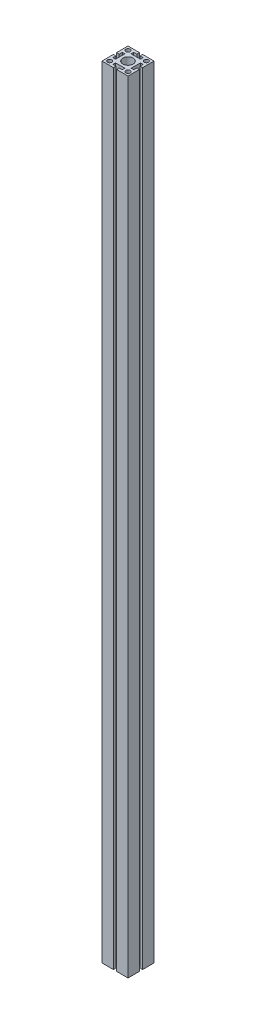
SolidWorks part; units mm, degrees
ref_plane "Front Plane" through (0, 0, 0) normal (0, 0, 1) x (1, 0, 0)
ref_plane "Top Plane" through (0, 0, 0) normal (0, 1, 0) x (1, 0, 0)
ref_plane "Right Plane" through (0, 0, 0) normal (1, 0, 0) x (0, 0, -1)
sketch "Sketch1" plane through (0, 0, 0) normal (0, 1, 0) x (1, 0, 0)
  line L1 (-25, -3) -> (-25, -25)
  line L6 (9, 20) -> (9, 15)
  line L7 (9, 20) -> (3, 20)
  line L8 (9, 15) -> (-9, 15)
  line L9 (3, 20) -> (3, 25)
  line L10 (-3, 25) -> (-25, 25)
  line L11 (-25, 25) -> (-25, 3)
  line L12 (-25, -25) -> (-3, -25)
  line L13 (25, -25) -> (25, -3)
  line L14 (3, 25) -> (25, 25)
  line L15 (-3, 20) -> (-3, 25)
  line L16 (-9, 20) -> (-9, 15)
  line L17 (3, -25) -> (25, -25)
  line L18 (25, 3) -> (25, 25)
  line L19 (-3, 20) -> (-9, 20)
  line L21 (-20, 9) -> (-15, 9)
  line L22 (-20, 9) -> (-20, 3)
  line L24 (-15, 9) -> (-15, -9)
  line L27 (-20, 3) -> (-25, 3)
  line L28 (20, -9) -> (15, -9)
  line L29 (20, -9) -> (20, -3)
  line L30 (15, -9) -> (15, 9)
  line L31 (20, -3) -> (25, -3)
  line L32 (20, 3) -> (25, 3)
  line L33 (-20, -3) -> (-25, -3)
  line L34 (20, 9) -> (15, 9)
  line L35 (20, 3) -> (20, 9)
  line L40 (-20, -9) -> (-15, -9)
  line L41 (-20, -3) -> (-20, -9)
  line L42 (-9, -20) -> (-9, -15)
  line L43 (-9, -20) -> (-3, -20)
  line L44 (-9, -15) -> (9, -15)
  line L45 (-3, -20) -> (-3, -25)
  line L46 (3, -20) -> (3, -25)
  line L47 (9, -20) -> (9, -15)
  line L48 (3, -20) -> (9, -20)
  circle A0 centre (0, 0) radius 10
  circle A1 centre (-17.6777, 17.6777) radius 4.1387
  circle A2 centre (17.6777, 17.6777) radius 4.1387
  circle A3 centre (17.6777, -17.6777) radius 4.1387
  circle A4 centre (-17.6777, -17.6777) radius 4.1387
  point P44 (0, 0)
  point P46 (0, 0)
  dimension "D1" = 4
extrude "Boss-Extrude1" add sketch "Sketch1" along normal blind 1500
